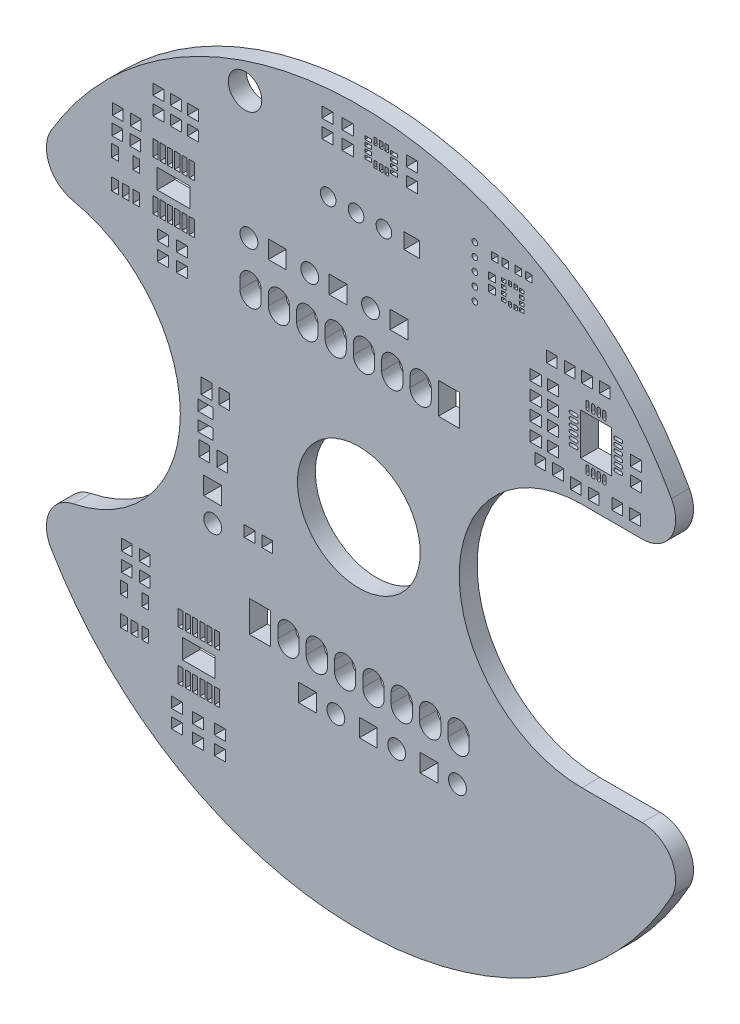
SolidWorks part; units mm, degrees
ref_plane "Plan de face" through (0, 0, 0) normal (0, 0, 1) x (1, 0, 0)
ref_plane "Plan de dessus" through (0, 0, 0) normal (0, 1, 0) x (1, 0, 0)
ref_plane "Plan de droite" through (0, 0, 0) normal (1, 0, 0) x (0, 0, -1)
sketch "Model" plane through (0, 0, 0) normal (0, 0, 1) x (1, 0, 0)
  line L0 (14.8, 23.5) -> (14.8, 23.2)
  line L1 (14.8, 23.2) -> (14.4, 23.2)
  line L2 (14.4, 23.2) -> (14.4, 23.5)
  line L3 (14.4, 23.5) -> (14.8, 23.5)
  line L4 (14.8, 24) -> (14.8, 23.7)
  line L5 (14.8, 23.7) -> (14.4, 23.7)
  line L6 (14.4, 23.7) -> (14.4, 24)
  line L7 (14.4, 24) -> (14.8, 24)
  line L8 (14.8, 24.5) -> (14.8, 24.2)
  line L9 (14.8, 24.2) -> (14.4, 24.2)
  line L10 (14.4, 24.2) -> (14.4, 24.5)
  line L11 (14.4, 24.5) -> (14.8, 24.5)
  line L12 (14.8, 25) -> (14.8, 24.7)
  line L13 (14.8, 24.7) -> (14.4, 24.7)
  line L14 (14.4, 24.7) -> (14.4, 25)
  line L15 (14.4, 25) -> (14.8, 25)
  line L16 (13.9, 25.1) -> (14.2, 25.1)
  line L17 (14.2, 25.1) -> (14.2, 24.7)
  line L18 (14.2, 24.7) -> (13.9, 24.7)
  line L19 (13.9, 24.7) -> (13.9, 25.1)
  line L20 (13.4, 25.1) -> (13.7, 25.1)
  line L21 (13.7, 25.1) -> (13.7, 24.7)
  line L22 (13.7, 24.7) -> (13.4, 24.7)
  line L23 (13.4, 24.7) -> (13.4, 25.1)
  line L24 (13.2, 25) -> (13.2, 24.7)
  line L25 (13.2, 24.7) -> (12.8, 24.7)
  line L26 (12.8, 24.7) -> (12.8, 25)
  line L27 (12.8, 25) -> (13.2, 25)
  line L28 (13.2, 24.5) -> (13.2, 24.2)
  line L29 (13.2, 24.2) -> (12.8, 24.2)
  line L30 (12.8, 24.2) -> (12.8, 24.5)
  line L31 (12.8, 24.5) -> (13.2, 24.5)
  line L32 (13.2, 24) -> (13.2, 23.7)
  line L33 (13.2, 23.7) -> (12.8, 23.7)
  line L34 (12.8, 23.7) -> (12.8, 24)
  line L35 (12.8, 24) -> (13.2, 24)
  line L36 (13.2, 23.5) -> (13.2, 23.2)
  line L37 (13.2, 23.2) -> (12.8, 23.2)
  line L38 (12.8, 23.2) -> (12.8, 23.5)
  line L39 (12.8, 23.5) -> (13.2, 23.5)
  line L40 (13.4, 23.5) -> (13.7, 23.5)
  line L41 (13.7, 23.5) -> (13.7, 23.1)
  line L42 (13.7, 23.1) -> (13.4, 23.1)
  line L43 (13.4, 23.1) -> (13.4, 23.5)
  line L44 (13.9, 23.5) -> (14.2, 23.5)
  line L45 (14.2, 23.5) -> (14.2, 23.1)
  line L46 (14.2, 23.1) -> (13.9, 23.1)
  line L47 (13.9, 23.1) -> (13.9, 23.5)
  line L48 (14.565, 25.93) -> (13.975, 25.93)
  line L49 (13.975, 25.93) -> (13.975, 26.57)
  line L50 (13.975, 26.57) -> (14.565, 26.57)
  line L51 (14.565, 26.57) -> (14.565, 25.93)
  line L52 (15.525, 25.93) -> (14.935, 25.93)
  line L53 (14.935, 25.93) -> (14.935, 26.57)
  line L54 (14.935, 26.57) -> (15.525, 26.57)
  line L55 (15.525, 26.57) -> (15.525, 25.93)
  line L56 (12.835, 26.57) -> (13.425, 26.57)
  line L57 (13.425, 26.57) -> (13.425, 25.93)
  line L58 (13.425, 25.93) -> (12.835, 25.93)
  line L59 (12.835, 25.93) -> (12.835, 26.57)
  line L60 (11.875, 26.57) -> (12.465, 26.57)
  line L61 (12.465, 26.57) -> (12.465, 25.93)
  line L62 (12.465, 25.93) -> (11.875, 25.93)
  line L63 (11.875, 25.93) -> (11.875, 26.57)
  line L64 (11.63, 24.285) -> (11.63, 24.875)
  line L65 (11.63, 24.875) -> (12.27, 24.875)
  line L66 (12.27, 24.875) -> (12.27, 24.285)
  line L67 (12.27, 24.285) -> (11.63, 24.285)
  line L68 (11.63, 23.325) -> (11.63, 23.915)
  line L69 (11.63, 23.915) -> (12.27, 23.915)
  line L70 (12.27, 23.915) -> (12.27, 23.325)
  line L71 (12.27, 23.325) -> (11.63, 23.325)
  line L72 (-12.725, -1.125) -> (-11.775, -1.125)
  line L73 (-11.775, -1.125) -> (-11.775, -2.475)
  line L74 (-11.775, -2.475) -> (-12.725, -2.475)
  line L75 (-12.725, -2.475) -> (-12.725, -1.125)
  line L76 (-14.325, -1.125) -> (-13.375, -1.125)
  line L77 (-13.375, -1.125) -> (-13.375, -2.475)
  line L78 (-13.375, -2.475) -> (-14.325, -2.475)
  line L79 (-14.325, -2.475) -> (-14.325, -1.125)
  line L80 (-12.525, 3.825) -> (-11.575, 3.825)
  line L81 (-11.575, 3.825) -> (-11.575, 2.475)
  line L82 (-11.575, 2.475) -> (-12.525, 2.475)
  line L83 (-12.525, 2.475) -> (-12.525, 3.825)
  line L84 (-14.125, 3.825) -> (-13.175, 3.825)
  line L85 (-13.175, 3.825) -> (-13.175, 2.475)
  line L86 (-13.175, 2.475) -> (-14.125, 2.475)
  line L87 (-14.125, 2.475) -> (-14.125, 3.825)
  line L88 (-13.075, 0.375) -> (-13.075, -0.575)
  line L89 (-13.075, -0.575) -> (-14.425, -0.575)
  line L90 (-14.425, -0.575) -> (-14.425, 0.375)
  line L91 (-14.425, 0.375) -> (-13.075, 0.375)
  line L92 (-13.075, 1.975) -> (-13.075, 1.025)
  line L93 (-13.075, 1.025) -> (-14.425, 1.025)
  line L94 (-14.425, 1.025) -> (-14.425, 1.975)
  line L95 (-14.425, 1.975) -> (-13.075, 1.975)
  line L96 (-21.55, 14.25) -> (-22.15, 14.25)
  line L97 (-22.15, 14.25) -> (-22.15, 15.35)
  line L98 (-22.15, 15.35) -> (-21.55, 15.35)
  line L99 (-21.55, 15.35) -> (-21.55, 14.25)
  line L100 (-20.6, 14.25) -> (-21.2, 14.25)
  line L101 (-21.2, 14.25) -> (-21.2, 15.35)
  line L102 (-21.2, 15.35) -> (-20.6, 15.35)
  line L103 (-20.6, 15.35) -> (-20.6, 14.25)
  line L104 (-19.65, 14.25) -> (-20.25, 14.25)
  line L105 (-20.25, 14.25) -> (-20.25, 15.35)
  line L106 (-20.25, 15.35) -> (-19.65, 15.35)
  line L107 (-19.65, 15.35) -> (-19.65, 14.25)
  line L108 (-19.65, 16.85) -> (-20.25, 16.85)
  line L109 (-20.25, 16.85) -> (-20.25, 17.95)
  line L110 (-20.25, 17.95) -> (-19.65, 17.95)
  line L111 (-19.65, 17.95) -> (-19.65, 16.85)
  line L112 (-21.55, 16.85) -> (-22.15, 16.85)
  line L113 (-22.15, 16.85) -> (-22.15, 17.95)
  line L114 (-22.15, 17.95) -> (-21.55, 17.95)
  line L115 (-21.55, 17.95) -> (-21.55, 16.85)
  line L116 (-20.75, -19.25) -> (-21.35, -19.25)
  line L117 (-21.35, -19.25) -> (-21.35, -18.15)
  line L118 (-21.35, -18.15) -> (-20.75, -18.15)
  line L119 (-20.75, -18.15) -> (-20.75, -19.25)
  line L120 (-19.8, -19.25) -> (-20.4, -19.25)
  line L121 (-20.4, -19.25) -> (-20.4, -18.15)
  line L122 (-20.4, -18.15) -> (-19.8, -18.15)
  line L123 (-19.8, -18.15) -> (-19.8, -19.25)
  line L124 (-18.85, -19.25) -> (-19.45, -19.25)
  line L125 (-19.45, -19.25) -> (-19.45, -18.15)
  line L126 (-19.45, -18.15) -> (-18.85, -18.15)
  line L127 (-18.85, -18.15) -> (-18.85, -19.25)
  line L128 (-18.85, -16.65) -> (-19.45, -16.65)
  line L129 (-19.45, -16.65) -> (-19.45, -15.55)
  line L130 (-19.45, -15.55) -> (-18.85, -15.55)
  line L131 (-18.85, -15.55) -> (-18.85, -16.65)
  line L132 (-20.75, -16.65) -> (-21.35, -16.65)
  line L133 (-21.35, -16.65) -> (-21.35, -15.55)
  line L134 (-21.35, -15.55) -> (-20.75, -15.55)
  line L135 (-20.75, -15.55) -> (-20.75, -16.65)
  line L136 (-18, 15.7505) -> (-18, 14.3255)
  line L137 (-18, 14.3255) -> (-18.45, 14.3255)
  line L138 (-18.45, 14.3255) -> (-18.45, 15.7505)
  line L139 (-18.45, 15.7505) -> (-18, 15.7505)
  line L140 (-17.35, 15.7505) -> (-17.35, 14.3255)
  line L141 (-17.35, 14.3255) -> (-17.8, 14.3255)
  line L142 (-17.8, 14.3255) -> (-17.8, 15.7505)
  line L143 (-17.8, 15.7505) -> (-17.35, 15.7505)
  line L144 (-16.7, 15.7505) -> (-16.7, 14.3255)
  line L145 (-16.7, 14.3255) -> (-17.15, 14.3255)
  line L146 (-17.15, 14.3255) -> (-17.15, 15.7505)
  line L147 (-17.15, 15.7505) -> (-16.7, 15.7505)
  line L148 (-16.05, 15.7505) -> (-16.05, 14.3255)
  line L149 (-16.05, 14.3255) -> (-16.5, 14.3255)
  line L150 (-16.5, 14.3255) -> (-16.5, 15.7505)
  line L151 (-16.5, 15.7505) -> (-16.05, 15.7505)
  line L152 (-15.4, 15.7505) -> (-15.4, 14.3255)
  line L153 (-15.4, 14.3255) -> (-15.85, 14.3255)
  line L154 (-15.85, 14.3255) -> (-15.85, 15.7505)
  line L155 (-15.85, 15.7505) -> (-15.4, 15.7505)
  line L156 (-14.75, 15.7505) -> (-14.75, 14.3255)
  line L157 (-14.75, 14.3255) -> (-15.2, 14.3255)
  line L158 (-15.2, 14.3255) -> (-15.2, 15.7505)
  line L159 (-15.2, 15.7505) -> (-14.75, 15.7505)
  line L160 (-14.75, 20.1745) -> (-14.75, 18.7495)
  line L161 (-14.75, 18.7495) -> (-15.2, 18.7495)
  line L162 (-15.2, 18.7495) -> (-15.2, 20.1745)
  line L163 (-15.2, 20.1745) -> (-14.75, 20.1745)
  line L164 (-15.4, 20.1745) -> (-15.4, 18.7495)
  line L165 (-15.4, 18.7495) -> (-15.85, 18.7495)
  line L166 (-15.85, 18.7495) -> (-15.85, 20.1745)
  line L167 (-15.85, 20.1745) -> (-15.4, 20.1745)
  line L168 (-16.05, 20.1745) -> (-16.05, 18.7495)
  line L169 (-16.05, 18.7495) -> (-16.5, 18.7495)
  line L170 (-16.5, 18.7495) -> (-16.5, 20.1745)
  line L171 (-16.5, 20.1745) -> (-16.05, 20.1745)
  line L172 (-16.7, 20.1745) -> (-16.7, 18.7495)
  line L173 (-16.7, 18.7495) -> (-17.15, 18.7495)
  line L174 (-17.15, 18.7495) -> (-17.15, 20.1745)
  line L175 (-17.15, 20.1745) -> (-16.7, 20.1745)
  line L176 (-17.35, 20.1745) -> (-17.35, 18.7495)
  line L177 (-17.35, 18.7495) -> (-17.8, 18.7495)
  line L178 (-17.8, 18.7495) -> (-17.8, 20.1745)
  line L179 (-17.8, 20.1745) -> (-17.35, 20.1745)
  line L180 (-18, 20.1745) -> (-18, 18.7495)
  line L181 (-18, 18.7495) -> (-18.45, 18.7495)
  line L182 (-18.45, 18.7495) -> (-18.45, 20.1745)
  line L183 (-18.45, 20.1745) -> (-18, 20.1745)
  line L184 (-18.0735, 18.1265) -> (-15.1265, 18.1265)
  line L185 (-15.1265, 18.1265) -> (-15.1265, 16.3735)
  line L186 (-15.1265, 16.3735) -> (-18.0735, 16.3735)
  line L187 (-18.0735, 16.3735) -> (-18.0735, 18.1265)
  line L188 (-12.95, -16.6005) -> (-12.95, -15.1755)
  line L189 (-12.95, -15.1755) -> (-12.5, -15.1755)
  line L190 (-12.5, -15.1755) -> (-12.5, -16.6005)
  line L191 (-12.5, -16.6005) -> (-12.95, -16.6005)
  line L192 (-13.6, -16.6005) -> (-13.6, -15.1755)
  line L193 (-13.6, -15.1755) -> (-13.15, -15.1755)
  line L194 (-13.15, -15.1755) -> (-13.15, -16.6005)
  line L195 (-13.15, -16.6005) -> (-13.6, -16.6005)
  line L196 (-14.25, -16.6005) -> (-14.25, -15.1755)
  line L197 (-14.25, -15.1755) -> (-13.8, -15.1755)
  line L198 (-13.8, -15.1755) -> (-13.8, -16.6005)
  line L199 (-13.8, -16.6005) -> (-14.25, -16.6005)
  line L200 (-14.9, -16.6005) -> (-14.9, -15.1755)
  line L201 (-14.9, -15.1755) -> (-14.45, -15.1755)
  line L202 (-14.45, -15.1755) -> (-14.45, -16.6005)
  line L203 (-14.45, -16.6005) -> (-14.9, -16.6005)
  line L204 (-15.55, -16.6005) -> (-15.55, -15.1755)
  line L205 (-15.55, -15.1755) -> (-15.1, -15.1755)
  line L206 (-15.1, -15.1755) -> (-15.1, -16.6005)
  line L207 (-15.1, -16.6005) -> (-15.55, -16.6005)
  line L208 (-16.2, -16.6005) -> (-16.2, -15.1755)
  line L209 (-16.2, -15.1755) -> (-15.75, -15.1755)
  line L210 (-15.75, -15.1755) -> (-15.75, -16.6005)
  line L211 (-15.75, -16.6005) -> (-16.2, -16.6005)
  line L212 (-16.2, -21.0245) -> (-16.2, -19.5995)
  line L213 (-16.2, -19.5995) -> (-15.75, -19.5995)
  line L214 (-15.75, -19.5995) -> (-15.75, -21.0245)
  line L215 (-15.75, -21.0245) -> (-16.2, -21.0245)
  line L216 (-15.55, -21.0245) -> (-15.55, -19.5995)
  line L217 (-15.55, -19.5995) -> (-15.1, -19.5995)
  line L218 (-15.1, -19.5995) -> (-15.1, -21.0245)
  line L219 (-15.1, -21.0245) -> (-15.55, -21.0245)
  line L220 (-14.9, -21.0245) -> (-14.9, -19.5995)
  line L221 (-14.9, -19.5995) -> (-14.45, -19.5995)
  line L222 (-14.45, -19.5995) -> (-14.45, -21.0245)
  line L223 (-14.45, -21.0245) -> (-14.9, -21.0245)
  line L224 (-14.25, -21.0245) -> (-14.25, -19.5995)
  line L225 (-14.25, -19.5995) -> (-13.8, -19.5995)
  line L226 (-13.8, -19.5995) -> (-13.8, -21.0245)
  line L227 (-13.8, -21.0245) -> (-14.25, -21.0245)
  line L228 (-13.6, -21.0245) -> (-13.6, -19.5995)
  line L229 (-13.6, -19.5995) -> (-13.15, -19.5995)
  line L230 (-13.15, -19.5995) -> (-13.15, -21.0245)
  line L231 (-13.15, -21.0245) -> (-13.6, -21.0245)
  line L232 (-12.95, -21.0245) -> (-12.95, -19.5995)
  line L233 (-12.95, -19.5995) -> (-12.5, -19.5995)
  line L234 (-12.5, -19.5995) -> (-12.5, -21.0245)
  line L235 (-12.5, -21.0245) -> (-12.95, -21.0245)
  line L236 (-12.8765, -18.9765) -> (-15.8235, -18.9765)
  line L237 (-15.8235, -18.9765) -> (-15.8235, -17.2235)
  line L238 (-15.8235, -17.2235) -> (-12.8765, -17.2235)
  line L239 (-12.8765, -17.2235) -> (-12.8765, -18.9765)
  line L240 (9.0325, 14.197) -> (9.0325, 11.403)
  line L241 (9.0325, 11.403) -> (7.1275, 11.403)
  line L242 (7.1275, 11.403) -> (7.1275, 14.197)
  line L243 (7.1275, 14.197) -> (9.0325, 14.197)
  line L244 (4.5875, 12.3555) -> (4.5875, 13.2445)
  line L245 (6.4925, 13.2445) -> (6.4925, 12.3555)
  line L246 (2.0475, 12.3555) -> (2.0475, 13.2445)
  line L247 (3.9525, 13.2445) -> (3.9525, 12.3555)
  line L248 (-0.4925, 12.3555) -> (-0.4925, 13.2445)
  line L249 (1.4125, 13.2445) -> (1.4125, 12.3555)
  line L250 (-3.0325, 12.3555) -> (-3.0325, 13.2445)
  line L251 (-1.1275, 13.2445) -> (-1.1275, 12.3555)
  line L252 (-5.5725, 12.3555) -> (-5.5725, 13.2445)
  line L253 (-3.6675, 13.2445) -> (-3.6675, 12.3555)
  line L254 (-8.1125, 12.3555) -> (-8.1125, 13.2445)
  line L255 (-6.2075, 13.2445) -> (-6.2075, 12.3555)
  line L256 (-10.6525, 12.3555) -> (-10.6525, 13.2445)
  line L257 (-8.7475, 13.2445) -> (-8.7475, 12.3555)
  line L258 (-9.8025, -13.997) -> (-9.8025, -11.203)
  line L259 (-9.8025, -11.203) -> (-7.8975, -11.203)
  line L260 (-7.8975, -11.203) -> (-7.8975, -13.997)
  line L261 (-7.8975, -13.997) -> (-9.8025, -13.997)
  line L262 (-5.3575, -12.1555) -> (-5.3575, -13.0445)
  line L263 (-7.2625, -13.0445) -> (-7.2625, -12.1555)
  line L264 (-2.8175, -12.1555) -> (-2.8175, -13.0445)
  line L265 (-4.7225, -13.0445) -> (-4.7225, -12.1555)
  line L266 (-0.2775, -12.1555) -> (-0.2775, -13.0445)
  line L267 (-2.1825, -13.0445) -> (-2.1825, -12.1555)
  line L268 (2.2625, -12.1555) -> (2.2625, -13.0445)
  line L269 (0.3575, -13.0445) -> (0.3575, -12.1555)
  line L270 (4.8025, -12.1555) -> (4.8025, -13.0445)
  line L271 (2.8975, -13.0445) -> (2.8975, -12.1555)
  line L272 (7.3425, -12.1555) -> (7.3425, -13.0445)
  line L273 (5.4375, -13.0445) -> (5.4375, -12.1555)
  line L274 (9.8825, -12.1555) -> (9.8825, -13.0445)
  line L275 (7.9775, -13.0445) -> (7.9775, -12.1555)
  line L276 (3.45, 28.4) -> (3.45, 28.1)
  line L277 (3.45, 28.1) -> (2.85, 28.1)
  line L278 (2.85, 28.1) -> (2.85, 28.4)
  line L279 (2.85, 28.4) -> (3.45, 28.4)
  line L280 (3.45, 28.9) -> (3.45, 28.6)
  line L281 (3.45, 28.6) -> (2.85, 28.6)
  line L282 (2.85, 28.6) -> (2.85, 28.9)
  line L283 (2.85, 28.9) -> (3.45, 28.9)
  line L284 (3.45, 29.4) -> (3.45, 29.1)
  line L285 (3.45, 29.1) -> (2.85, 29.1)
  line L286 (2.85, 29.1) -> (2.85, 29.4)
  line L287 (2.85, 29.4) -> (3.45, 29.4)
  line L288 (3.45, 29.9) -> (3.45, 29.6)
  line L289 (3.45, 29.6) -> (2.85, 29.6)
  line L290 (2.85, 29.6) -> (2.85, 29.9)
  line L291 (2.85, 29.9) -> (3.45, 29.9)
  line L292 (2.35, 30.2) -> (2.65, 30.2)
  line L293 (2.65, 30.2) -> (2.65, 29.6)
  line L294 (2.65, 29.6) -> (2.35, 29.6)
  line L295 (2.35, 29.6) -> (2.35, 30.2)
  line L296 (1.85, 30.2) -> (2.15, 30.2)
  line L297 (2.15, 30.2) -> (2.15, 29.6)
  line L298 (2.15, 29.6) -> (1.85, 29.6)
  line L299 (1.85, 29.6) -> (1.85, 30.2)
  line L300 (1.35, 30.2) -> (1.65, 30.2)
  line L301 (1.65, 30.2) -> (1.65, 29.6)
  line L302 (1.65, 29.6) -> (1.35, 29.6)
  line L303 (1.35, 29.6) -> (1.35, 30.2)
  line L304 (1.15, 29.9) -> (1.15, 29.6)
  line L305 (1.15, 29.6) -> (0.55, 29.6)
  line L306 (0.55, 29.6) -> (0.55, 29.9)
  line L307 (0.55, 29.9) -> (1.15, 29.9)
  line L308 (1.15, 29.4) -> (1.15, 29.1)
  line L309 (1.15, 29.1) -> (0.55, 29.1)
  line L310 (0.55, 29.1) -> (0.55, 29.4)
  line L311 (0.55, 29.4) -> (1.15, 29.4)
  line L312 (1.15, 28.9) -> (1.15, 28.6)
  line L313 (1.15, 28.6) -> (0.55, 28.6)
  line L314 (0.55, 28.6) -> (0.55, 28.9)
  line L315 (0.55, 28.9) -> (1.15, 28.9)
  line L316 (1.15, 28.4) -> (1.15, 28.1)
  line L317 (1.15, 28.1) -> (0.55, 28.1)
  line L318 (0.55, 28.1) -> (0.55, 28.4)
  line L319 (0.55, 28.4) -> (1.15, 28.4)
  line L320 (1.35, 28.4) -> (1.65, 28.4)
  line L321 (1.65, 28.4) -> (1.65, 27.8)
  line L322 (1.65, 27.8) -> (1.35, 27.8)
  line L323 (1.35, 27.8) -> (1.35, 28.4)
  line L324 (1.85, 28.4) -> (2.15, 28.4)
  line L325 (2.15, 28.4) -> (2.15, 27.8)
  line L326 (2.15, 27.8) -> (1.85, 27.8)
  line L327 (1.85, 27.8) -> (1.85, 28.4)
  line L328 (2.35, 28.4) -> (2.65, 28.4)
  line L329 (2.65, 28.4) -> (2.65, 27.8)
  line L330 (2.65, 27.8) -> (2.35, 27.8)
  line L331 (2.35, 27.8) -> (2.35, 28.4)
  line L332 (23, 15.3) -> (23.5, 15.3)
  line L333 (23.5, 15) -> (23, 15)
  line L334 (23, 15.8) -> (23.5, 15.8)
  line L335 (23.5, 15.5) -> (23, 15.5)
  line L336 (23, 16.3) -> (23.5, 16.3)
  line L337 (23.5, 16) -> (23, 16)
  line L338 (23, 16.8) -> (23.5, 16.8)
  line L339 (23.5, 16.5) -> (23, 16.5)
  line L340 (23, 17.3) -> (23.5, 17.3)
  line L341 (23.5, 17) -> (23, 17)
  line L342 (23, 17.8) -> (23.5, 17.8)
  line L343 (23.5, 17.5) -> (23, 17.5)
  line L344 (21.85, 18.65) -> (21.85, 19.15)
  line L345 (22.15, 19.15) -> (22.15, 18.65)
  line L346 (21.35, 18.65) -> (21.35, 19.15)
  line L347 (21.65, 19.15) -> (21.65, 18.65)
  line L348 (20.85, 18.65) -> (20.85, 19.15)
  line L349 (21.15, 19.15) -> (21.15, 18.65)
  line L350 (20.35, 18.65) -> (20.35, 19.15)
  line L351 (20.65, 19.15) -> (20.65, 18.65)
  line L352 (19, 17.8) -> (19.5, 17.8)
  line L353 (19.5, 17.5) -> (19, 17.5)
  line L354 (19, 17.3) -> (19.5, 17.3)
  line L355 (19.5, 17) -> (19, 17)
  line L356 (19, 16.8) -> (19.5, 16.8)
  line L357 (19.5, 16.5) -> (19, 16.5)
  line L358 (19, 16.3) -> (19.5, 16.3)
  line L359 (19.5, 16) -> (19, 16)
  line L360 (19, 15.8) -> (19.5, 15.8)
  line L361 (19.5, 15.5) -> (19, 15.5)
  line L362 (19, 15.3) -> (19.5, 15.3)
  line L363 (19.5, 15) -> (19, 15)
  line L364 (20.35, 13.65) -> (20.35, 14.15)
  line L365 (20.65, 14.15) -> (20.65, 13.65)
  line L366 (20.85, 13.65) -> (20.85, 14.15)
  line L367 (21.15, 14.15) -> (21.15, 13.65)
  line L368 (21.35, 13.65) -> (21.35, 14.15)
  line L369 (21.65, 14.15) -> (21.65, 13.65)
  line L370 (21.85, 13.65) -> (21.85, 14.15)
  line L371 (22.15, 14.15) -> (22.15, 13.65)
  line L372 (22.625, 18.275) -> (22.625, 14.525)
  line L373 (22.625, 14.525) -> (19.875, 14.525)
  line L374 (19.875, 14.525) -> (19.875, 18.275)
  line L375 (19.875, 18.275) -> (22.625, 18.275)
  line L376 (-9.325, -6.7) -> (-10.275, -6.7)
  line L377 (-10.275, -6.7) -> (-10.275, -5.7)
  line L378 (-10.275, -5.7) -> (-9.325, -5.7)
  line L379 (-9.325, -5.7) -> (-9.325, -6.7)
  line L380 (-7.725, -6.7) -> (-8.675, -6.7)
  line L381 (-8.675, -6.7) -> (-8.675, -5.7)
  line L382 (-8.675, -5.7) -> (-7.725, -5.7)
  line L383 (-7.725, -5.7) -> (-7.725, -6.7)
  line L384 (-21.125, 20.15) -> (-22.075, 20.15)
  line L385 (-22.075, 20.15) -> (-22.075, 21.15)
  line L386 (-22.075, 21.15) -> (-21.125, 21.15)
  line L387 (-21.125, 21.15) -> (-21.125, 20.15)
  line L388 (-19.525, 20.15) -> (-20.475, 20.15)
  line L389 (-20.475, 20.15) -> (-20.475, 21.15)
  line L390 (-20.475, 21.15) -> (-19.525, 21.15)
  line L391 (-19.525, 21.15) -> (-19.525, 20.15)
  line L392 (-20.325, -13.25) -> (-21.275, -13.25)
  line L393 (-21.275, -13.25) -> (-21.275, -12.25)
  line L394 (-21.275, -12.25) -> (-20.325, -12.25)
  line L395 (-20.325, -12.25) -> (-20.325, -13.25)
  line L396 (-18.725, -13.25) -> (-19.675, -13.25)
  line L397 (-19.675, -13.25) -> (-19.675, -12.25)
  line L398 (-19.675, -12.25) -> (-18.725, -12.25)
  line L399 (-18.725, -12.25) -> (-18.725, -13.25)
  line L400 (-21.175, 18.55) -> (-22.125, 18.55)
  line L401 (-22.125, 18.55) -> (-22.125, 19.55)
  line L402 (-22.125, 19.55) -> (-21.175, 19.55)
  line L403 (-21.175, 19.55) -> (-21.175, 18.55)
  line L404 (-19.575, 18.55) -> (-20.525, 18.55)
  line L405 (-20.525, 18.55) -> (-20.525, 19.55)
  line L406 (-20.525, 19.55) -> (-19.575, 19.55)
  line L407 (-19.575, 19.55) -> (-19.575, 18.55)
  line L408 (-20.325, -14.9) -> (-21.275, -14.9)
  line L409 (-21.275, -14.9) -> (-21.275, -13.9)
  line L410 (-21.275, -13.9) -> (-20.325, -13.9)
  line L411 (-20.325, -13.9) -> (-20.325, -14.9)
  line L412 (-18.725, -14.9) -> (-19.675, -14.9)
  line L413 (-19.675, -14.9) -> (-19.675, -13.9)
  line L414 (-19.675, -13.9) -> (-18.725, -13.9)
  line L415 (-18.725, -13.9) -> (-18.725, -14.9)
  line L416 (-18.45, 23.525) -> (-18.45, 24.475)
  line L417 (-18.45, 24.475) -> (-17.45, 24.475)
  line L418 (-17.45, 24.475) -> (-17.45, 23.525)
  line L419 (-17.45, 23.525) -> (-18.45, 23.525)
  line L420 (-18.45, 21.925) -> (-18.45, 22.875)
  line L421 (-18.45, 22.875) -> (-17.45, 22.875)
  line L422 (-17.45, 22.875) -> (-17.45, 21.925)
  line L423 (-17.45, 21.925) -> (-18.45, 21.925)
  line L424 (20.925, 20.4) -> (19.975, 20.4)
  line L425 (19.975, 20.4) -> (19.975, 21.4)
  line L426 (19.975, 21.4) -> (20.925, 21.4)
  line L427 (20.925, 21.4) -> (20.925, 20.4)
  line L428 (22.525, 20.4) -> (21.575, 20.4)
  line L429 (21.575, 20.4) -> (21.575, 21.4)
  line L430 (21.575, 21.4) -> (22.525, 21.4)
  line L431 (22.525, 21.4) -> (22.525, 20.4)
  line L432 (-15.9, 22.875) -> (-15.9, 21.925)
  line L433 (-15.9, 21.925) -> (-16.9, 21.925)
  line L434 (-16.9, 21.925) -> (-16.9, 22.875)
  line L435 (-16.9, 22.875) -> (-15.9, 22.875)
  line L436 (-15.9, 24.475) -> (-15.9, 23.525)
  line L437 (-15.9, 23.525) -> (-16.9, 23.525)
  line L438 (-16.9, 23.525) -> (-16.9, 24.475)
  line L439 (-16.9, 24.475) -> (-15.9, 24.475)
  line L440 (-14.9, -23.475) -> (-14.9, -22.525)
  line L441 (-14.9, -22.525) -> (-13.9, -22.525)
  line L442 (-13.9, -22.525) -> (-13.9, -23.475)
  line L443 (-13.9, -23.475) -> (-14.9, -23.475)
  line L444 (-14.9, -25.075) -> (-14.9, -24.125)
  line L445 (-14.9, -24.125) -> (-13.9, -24.125)
  line L446 (-13.9, -24.125) -> (-13.9, -25.075)
  line L447 (-13.9, -25.075) -> (-14.9, -25.075)
  line L448 (-18.05, 12.425) -> (-18.05, 13.375)
  line L449 (-18.05, 13.375) -> (-17.05, 13.375)
  line L450 (-17.05, 13.375) -> (-17.05, 12.425)
  line L451 (-17.05, 12.425) -> (-18.05, 12.425)
  line L452 (-18.05, 10.825) -> (-18.05, 11.775)
  line L453 (-18.05, 11.775) -> (-17.05, 11.775)
  line L454 (-17.05, 11.775) -> (-17.05, 10.825)
  line L455 (-17.05, 10.825) -> (-18.05, 10.825)
  line L456 (-15.35, 11.775) -> (-15.35, 10.825)
  line L457 (-15.35, 10.825) -> (-16.35, 10.825)
  line L458 (-16.35, 10.825) -> (-16.35, 11.775)
  line L459 (-16.35, 11.775) -> (-15.35, 11.775)
  line L460 (-15.35, 13.375) -> (-15.35, 12.425)
  line L461 (-15.35, 12.425) -> (-16.35, 12.425)
  line L462 (-16.35, 12.425) -> (-16.35, 13.375)
  line L463 (-16.35, 13.375) -> (-15.35, 13.375)
  line L464 (-15.35, 23.525) -> (-15.35, 24.475)
  line L465 (-15.35, 24.475) -> (-14.35, 24.475)
  line L466 (-14.35, 24.475) -> (-14.35, 23.525)
  line L467 (-14.35, 23.525) -> (-15.35, 23.525)
  line L468 (-15.35, 21.925) -> (-15.35, 22.875)
  line L469 (-15.35, 22.875) -> (-14.35, 22.875)
  line L470 (-14.35, 22.875) -> (-14.35, 21.925)
  line L471 (-14.35, 21.925) -> (-15.35, 21.925)
  line L472 (4.25, 29.325) -> (4.25, 30.275)
  line L473 (4.25, 30.275) -> (5.25, 30.275)
  line L474 (5.25, 30.275) -> (5.25, 29.325)
  line L475 (5.25, 29.325) -> (4.25, 29.325)
  line L476 (4.25, 27.725) -> (4.25, 28.675)
  line L477 (4.25, 28.675) -> (5.25, 28.675)
  line L478 (5.25, 28.675) -> (5.25, 27.725)
  line L479 (5.25, 27.725) -> (4.25, 27.725)
  line L480 (-2.3, 28.675) -> (-2.3, 27.725)
  line L481 (-2.3, 27.725) -> (-3.3, 27.725)
  line L482 (-3.3, 27.725) -> (-3.3, 28.675)
  line L483 (-3.3, 28.675) -> (-2.3, 28.675)
  line L484 (-2.3, 30.275) -> (-2.3, 29.325)
  line L485 (-2.3, 29.325) -> (-3.3, 29.325)
  line L486 (-3.3, 29.325) -> (-3.3, 30.275)
  line L487 (-3.3, 30.275) -> (-2.3, 30.275)
  line L488 (-0.5, 28.675) -> (-0.5, 27.725)
  line L489 (-0.5, 27.725) -> (-1.5, 27.725)
  line L490 (-1.5, 27.725) -> (-1.5, 28.675)
  line L491 (-1.5, 28.675) -> (-0.5, 28.675)
  line L492 (-0.5, 30.275) -> (-0.5, 29.325)
  line L493 (-0.5, 29.325) -> (-1.5, 29.325)
  line L494 (-1.5, 29.325) -> (-1.5, 30.275)
  line L495 (-1.5, 30.275) -> (-0.5, 30.275)
  line L496 (16.725, 11.95) -> (15.775, 11.95)
  line L497 (15.775, 11.95) -> (15.775, 12.95)
  line L498 (15.775, 12.95) -> (16.725, 12.95)
  line L499 (16.725, 12.95) -> (16.725, 11.95)
  line L500 (18.325, 11.95) -> (17.375, 11.95)
  line L501 (17.375, 11.95) -> (17.375, 12.95)
  line L502 (17.375, 12.95) -> (18.325, 12.95)
  line L503 (18.325, 12.95) -> (18.325, 11.95)
  line L504 (19.925, 11.65) -> (18.975, 11.65)
  line L505 (18.975, 11.65) -> (18.975, 12.65)
  line L506 (18.975, 12.65) -> (19.925, 12.65)
  line L507 (19.925, 12.65) -> (19.925, 11.65)
  line L508 (21.525, 11.65) -> (20.575, 11.65)
  line L509 (20.575, 11.65) -> (20.575, 12.65)
  line L510 (20.575, 12.65) -> (21.525, 12.65)
  line L511 (21.525, 12.65) -> (21.525, 11.65)
  line L512 (17.775, 20.4) -> (16.825, 20.4)
  line L513 (16.825, 20.4) -> (16.825, 21.4)
  line L514 (16.825, 21.4) -> (17.775, 21.4)
  line L515 (17.775, 21.4) -> (17.775, 20.4)
  line L516 (19.375, 20.4) -> (18.425, 20.4)
  line L517 (18.425, 20.4) -> (18.425, 21.4)
  line L518 (18.425, 21.4) -> (19.375, 21.4)
  line L519 (19.375, 21.4) -> (19.375, 20.4)
  line L520 (25.35, 15.475) -> (25.35, 14.525)
  line L521 (25.35, 14.525) -> (24.35, 14.525)
  line L522 (24.35, 14.525) -> (24.35, 15.475)
  line L523 (24.35, 15.475) -> (25.35, 15.475)
  line L524 (25.35, 17.075) -> (25.35, 16.125)
  line L525 (25.35, 16.125) -> (24.35, 16.125)
  line L526 (24.35, 16.125) -> (24.35, 17.075)
  line L527 (24.35, 17.075) -> (25.35, 17.075)
  line L528 (24.275, 12.9) -> (25.225, 12.9)
  line L529 (25.225, 12.9) -> (25.225, 11.9)
  line L530 (25.225, 11.9) -> (24.275, 11.9)
  line L531 (24.275, 11.9) -> (24.275, 12.9)
  line L532 (22.675, 12.9) -> (23.625, 12.9)
  line L533 (23.625, 12.9) -> (23.625, 11.9)
  line L534 (23.625, 11.9) -> (22.675, 11.9)
  line L535 (22.675, 11.9) -> (22.675, 12.9)
  line L536 (16.35, 14.475) -> (16.35, 13.525)
  line L537 (16.35, 13.525) -> (15.35, 13.525)
  line L538 (15.35, 13.525) -> (15.35, 14.475)
  line L539 (15.35, 14.475) -> (16.35, 14.475)
  line L540 (16.35, 16.075) -> (16.35, 15.125)
  line L541 (16.35, 15.125) -> (15.35, 15.125)
  line L542 (15.35, 15.125) -> (15.35, 16.075)
  line L543 (15.35, 16.075) -> (16.35, 16.075)
  line L544 (17.9, 14.475) -> (17.9, 13.525)
  line L545 (17.9, 13.525) -> (16.9, 13.525)
  line L546 (16.9, 13.525) -> (16.9, 14.475)
  line L547 (16.9, 14.475) -> (17.9, 14.475)
  line L548 (17.9, 16.075) -> (17.9, 15.125)
  line L549 (17.9, 15.125) -> (16.9, 15.125)
  line L550 (16.9, 15.125) -> (16.9, 16.075)
  line L551 (16.9, 16.075) -> (17.9, 16.075)
  line L552 (16.35, 17.625) -> (16.35, 16.675)
  line L553 (16.35, 16.675) -> (15.35, 16.675)
  line L554 (15.35, 16.675) -> (15.35, 17.625)
  line L555 (15.35, 17.625) -> (16.35, 17.625)
  line L556 (16.35, 19.225) -> (16.35, 18.275)
  line L557 (16.35, 18.275) -> (15.35, 18.275)
  line L558 (15.35, 18.275) -> (15.35, 19.225)
  line L559 (15.35, 19.225) -> (16.35, 19.225)
  line L560 (17.9, 17.625) -> (17.9, 16.675)
  line L561 (17.9, 16.675) -> (16.9, 16.675)
  line L562 (16.9, 16.675) -> (16.9, 17.625)
  line L563 (16.9, 17.625) -> (17.9, 17.625)
  line L564 (17.9, 19.225) -> (17.9, 18.275)
  line L565 (17.9, 18.275) -> (16.9, 18.275)
  line L566 (16.9, 18.275) -> (16.9, 19.225)
  line L567 (16.9, 19.225) -> (17.9, 19.225)
  line L568 (-16.8, -23.225) -> (-16.8, -22.275)
  line L569 (-16.8, -22.275) -> (-15.8, -22.275)
  line L570 (-15.8, -22.275) -> (-15.8, -23.225)
  line L571 (-15.8, -23.225) -> (-16.8, -23.225)
  line L572 (-16.8, -24.825) -> (-16.8, -23.875)
  line L573 (-16.8, -23.875) -> (-15.8, -23.875)
  line L574 (-15.8, -23.875) -> (-15.8, -24.825)
  line L575 (-15.8, -24.825) -> (-16.8, -24.825)
  line L576 (-11.95, -24.025) -> (-11.95, -24.975)
  line L577 (-11.95, -24.975) -> (-12.95, -24.975)
  line L578 (-12.95, -24.975) -> (-12.95, -24.025)
  line L579 (-12.95, -24.025) -> (-11.95, -24.025)
  line L580 (-11.95, -22.425) -> (-11.95, -23.375)
  line L581 (-11.95, -23.375) -> (-12.95, -23.375)
  line L582 (-12.95, -23.375) -> (-12.95, -22.425)
  line L583 (-12.95, -22.425) -> (-11.95, -22.425)
  line L584 (5.45, 24.2) -> (5.45, 22.8)
  line L585 (5.45, 22.8) -> (4.05, 22.8)
  line L586 (4.05, 22.8) -> (4.05, 24.2)
  line L587 (4.05, 24.2) -> (5.45, 24.2)
  line L588 (-6.51, 17.55) -> (-6.51, 15.95)
  line L589 (-6.51, 15.95) -> (-8.11, 15.95)
  line L590 (-8.11, 15.95) -> (-8.11, 17.55)
  line L591 (-8.11, 17.55) -> (-6.51, 17.55)
  line L592 (-1.06, 17.55) -> (-1.06, 15.95)
  line L593 (-1.06, 15.95) -> (-2.66, 15.95)
  line L594 (-2.66, 15.95) -> (-2.66, 17.55)
  line L595 (-2.66, 17.55) -> (-1.06, 17.55)
  line L596 (4.39, 17.55) -> (4.39, 15.95)
  line L597 (4.39, 15.95) -> (2.79, 15.95)
  line L598 (2.79, 15.95) -> (2.79, 17.55)
  line L599 (2.79, 17.55) -> (4.39, 17.55)
  line L600 (5.5, -17.1) -> (5.5, -15.5)
  line L601 (5.5, -15.5) -> (7.1, -15.5)
  line L602 (7.1, -15.5) -> (7.1, -17.1)
  line L603 (7.1, -17.1) -> (5.5, -17.1)
  line L604 (0.05, -17.1) -> (0.05, -15.5)
  line L605 (0.05, -15.5) -> (1.65, -15.5)
  line L606 (1.65, -15.5) -> (1.65, -17.1)
  line L607 (1.65, -17.1) -> (0.05, -17.1)
  line L608 (-5.4, -17.1) -> (-5.4, -15.5)
  line L609 (-5.4, -15.5) -> (-3.8, -15.5)
  line L610 (-3.8, -15.5) -> (-3.8, -17.1)
  line L611 (-3.8, -17.1) -> (-5.4, -17.1)
  line L612 (-13.9, -3.68) -> (-12.3, -3.68)
  line L613 (-12.3, -3.68) -> (-12.3, -5.28)
  line L614 (-12.3, -5.28) -> (-13.9, -5.28)
  line L615 (-13.9, -5.28) -> (-13.9, -3.68)
  line L616 (25.3969, -11) -> (20, -11)
  line L617 (20, 11) -> (25.3969, 11)
  circle A1 centre (10.4, 21.95) radius 0.254
  circle A2 centre (10.4, 23.1) radius 0.254
  circle A3 centre (10.4, 24.25) radius 0.254
  circle A4 centre (10.4, 25.4) radius 0.254
  circle A5 centre (10.4, 26.55) radius 0.254
  circle A6 centre (-10.2, 28) radius 1.5
  circle A7 centre (2.25, 23.5) radius 0.7
  circle A8 centre (-0.25, 23.5) radius 0.7
  circle A9 centre (-2.75, 23.5) radius 0.7
  circle A10 centre (-9.85, 16.75) radius 0.8
  circle A11 centre (-4.4, 16.75) radius 0.8
  circle A12 centre (1.05, 16.75) radius 0.8
  circle A13 centre (8.84, -16.3) radius 0.8
  circle A14 centre (3.39, -16.3) radius 0.8
  circle A15 centre (-2.06, -16.3) radius 0.8
  circle A16 centre (-13.1, -7.02) radius 0.8
  arc A17 (6.4925, 13.2445) -> (4.5875, 13.2445) centre (5.54, 13.2445) ccw
  arc A18 (4.5875, 12.3555) -> (6.4925, 12.3555) centre (5.54, 12.3555) ccw
  arc A19 (3.9525, 13.2445) -> (2.0475, 13.2445) centre (3, 13.2445) ccw
  arc A20 (2.0475, 12.3555) -> (3.9525, 12.3555) centre (3, 12.3555) ccw
  arc A21 (1.4125, 13.2445) -> (-0.4925, 13.2445) centre (0.46, 13.2445) ccw
  arc A22 (-0.4925, 12.3555) -> (1.4125, 12.3555) centre (0.46, 12.3555) ccw
  arc A23 (-1.1275, 13.2445) -> (-3.0325, 13.2445) centre (-2.08, 13.2445) ccw
  arc A24 (-3.0325, 12.3555) -> (-1.1275, 12.3555) centre (-2.08, 12.3555) ccw
  arc A25 (-3.6675, 13.2445) -> (-5.5725, 13.2445) centre (-4.62, 13.2445) ccw
  arc A26 (-5.5725, 12.3555) -> (-3.6675, 12.3555) centre (-4.62, 12.3555) ccw
  arc A27 (-6.2075, 13.2445) -> (-8.1125, 13.2445) centre (-7.16, 13.2445) ccw
  arc A28 (-8.1125, 12.3555) -> (-6.2075, 12.3555) centre (-7.16, 12.3555) ccw
  arc A29 (-8.7475, 13.2445) -> (-10.6525, 13.2445) centre (-9.7, 13.2445) ccw
  arc A30 (-10.6525, 12.3555) -> (-8.7475, 12.3555) centre (-9.7, 12.3555) ccw
  arc A31 (-7.2625, -13.0445) -> (-5.3575, -13.0445) centre (-6.31, -13.0445) ccw
  arc A32 (-5.3575, -12.1555) -> (-7.2625, -12.1555) centre (-6.31, -12.1555) ccw
  arc A33 (-4.7225, -13.0445) -> (-2.8175, -13.0445) centre (-3.77, -13.0445) ccw
  arc A34 (-2.8175, -12.1555) -> (-4.7225, -12.1555) centre (-3.77, -12.1555) ccw
  arc A35 (-2.1825, -13.0445) -> (-0.2775, -13.0445) centre (-1.23, -13.0445) ccw
  arc A36 (-0.2775, -12.1555) -> (-2.1825, -12.1555) centre (-1.23, -12.1555) ccw
  arc A37 (0.3575, -13.0445) -> (2.2625, -13.0445) centre (1.31, -13.0445) ccw
  arc A38 (2.2625, -12.1555) -> (0.3575, -12.1555) centre (1.31, -12.1555) ccw
  arc A39 (2.8975, -13.0445) -> (4.8025, -13.0445) centre (3.85, -13.0445) ccw
  arc A40 (4.8025, -12.1555) -> (2.8975, -12.1555) centre (3.85, -12.1555) ccw
  arc A41 (5.4375, -13.0445) -> (7.3425, -13.0445) centre (6.39, -13.0445) ccw
  arc A42 (7.3425, -12.1555) -> (5.4375, -12.1555) centre (6.39, -12.1555) ccw
  arc A43 (7.9775, -13.0445) -> (9.8825, -13.0445) centre (8.93, -13.0445) ccw
  arc A44 (9.8825, -12.1555) -> (7.9775, -12.1555) centre (8.93, -12.1555) ccw
  arc A45 (23.5, 15) -> (23.5, 15.3) centre (23.5, 15.15) ccw
  arc A46 (23, 15.3) -> (23, 15) centre (23, 15.15) ccw
  arc A47 (23.5, 15.5) -> (23.5, 15.8) centre (23.5, 15.65) ccw
  arc A48 (23, 15.8) -> (23, 15.5) centre (23, 15.65) ccw
  arc A49 (23.5, 16) -> (23.5, 16.3) centre (23.5, 16.15) ccw
  arc A50 (23, 16.3) -> (23, 16) centre (23, 16.15) ccw
  arc A51 (23.5, 16.5) -> (23.5, 16.8) centre (23.5, 16.65) ccw
  arc A52 (23, 16.8) -> (23, 16.5) centre (23, 16.65) ccw
  arc A53 (23.5, 17) -> (23.5, 17.3) centre (23.5, 17.15) ccw
  arc A54 (23, 17.3) -> (23, 17) centre (23, 17.15) ccw
  arc A55 (23.5, 17.5) -> (23.5, 17.8) centre (23.5, 17.65) ccw
  arc A56 (23, 17.8) -> (23, 17.5) centre (23, 17.65) ccw
  arc A57 (22.15, 19.15) -> (21.85, 19.15) centre (22, 19.15) ccw
  arc A58 (21.85, 18.65) -> (22.15, 18.65) centre (22, 18.65) ccw
  arc A59 (21.65, 19.15) -> (21.35, 19.15) centre (21.5, 19.15) ccw
  arc A60 (21.35, 18.65) -> (21.65, 18.65) centre (21.5, 18.65) ccw
  arc A61 (21.15, 19.15) -> (20.85, 19.15) centre (21, 19.15) ccw
  arc A62 (20.85, 18.65) -> (21.15, 18.65) centre (21, 18.65) ccw
  arc A63 (20.65, 19.15) -> (20.35, 19.15) centre (20.5, 19.15) ccw
  arc A64 (20.35, 18.65) -> (20.65, 18.65) centre (20.5, 18.65) ccw
  arc A65 (19.5, 17.5) -> (19.5, 17.8) centre (19.5, 17.65) ccw
  arc A66 (19, 17.8) -> (19, 17.5) centre (19, 17.65) ccw
  arc A67 (19.5, 17) -> (19.5, 17.3) centre (19.5, 17.15) ccw
  arc A68 (19, 17.3) -> (19, 17) centre (19, 17.15) ccw
  arc A69 (19.5, 16.5) -> (19.5, 16.8) centre (19.5, 16.65) ccw
  arc A70 (19, 16.8) -> (19, 16.5) centre (19, 16.65) ccw
  arc A71 (19.5, 16) -> (19.5, 16.3) centre (19.5, 16.15) ccw
  arc A72 (19, 16.3) -> (19, 16) centre (19, 16.15) ccw
  arc A73 (19.5, 15.5) -> (19.5, 15.8) centre (19.5, 15.65) ccw
  arc A74 (19, 15.8) -> (19, 15.5) centre (19, 15.65) ccw
  arc A75 (19.5, 15) -> (19.5, 15.3) centre (19.5, 15.15) ccw
  arc A76 (19, 15.3) -> (19, 15) centre (19, 15.15) ccw
  arc A77 (20.65, 14.15) -> (20.35, 14.15) centre (20.5, 14.15) ccw
  arc A78 (20.35, 13.65) -> (20.65, 13.65) centre (20.5, 13.65) ccw
  arc A79 (21.15, 14.15) -> (20.85, 14.15) centre (21, 14.15) ccw
  arc A80 (20.85, 13.65) -> (21.15, 13.65) centre (21, 13.65) ccw
  arc A81 (21.65, 14.15) -> (21.35, 14.15) centre (21.5, 14.15) ccw
  arc A82 (21.35, 13.65) -> (21.65, 13.65) centre (21.5, 13.65) ccw
  arc A83 (22.15, 14.15) -> (21.85, 14.15) centre (22, 14.15) ccw
  arc A84 (21.85, 13.65) -> (22.15, 13.65) centre (22, 13.65) ccw
  arc A85 (-25.6, -11.7576) -> (-25.6, 11.7575) centre (-27.9998, 0) ccw
  arc A86 (-27.5862, 16.2173) -> (-25.6, 11.7575) centre (-25, 14.6969) ccw
  arc A87 (28.0241, -15.4483) -> (25.3969, -11) centre (25.3969, -14) ccw
  arc A88 (20, 11) -> (20, -11) centre (20, 0) ccw
  arc A89 (25.3969, 11) -> (28.0241, 15.4483) centre (25.3968, 14) ccw
  arc A90 (28.0241, 15.4483) -> (-27.5862, 16.2173) centre (0, 0) ccw
  arc A91 (-25.6, -11.7576) -> (-27.5862, -16.2173) centre (-25, -14.697) ccw
  arc A92 (-27.5862, -16.2173) -> (28.0241, -15.4483) centre (0, 0) ccw
  circle A93 centre (0, 0) radius 5.5
extrude "Boss.-Extru.1" add sketch "Model" along normal blind 1.6
